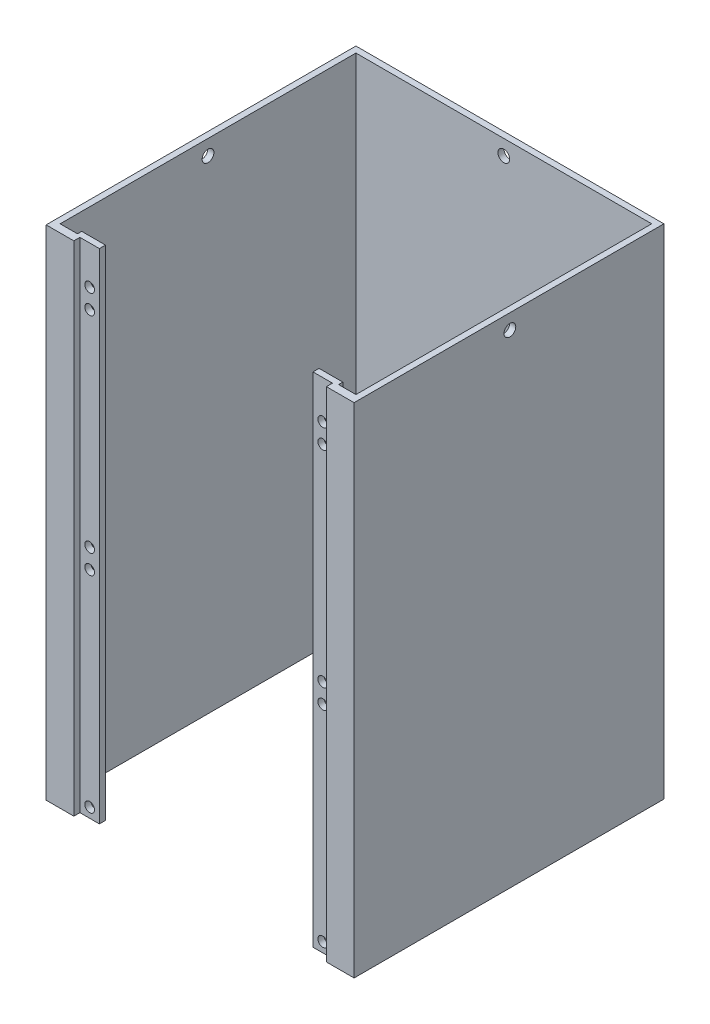
SolidWorks part; units mm, degrees
ref_plane "Front Plane" through (0, 0, 0) normal (0, 0, 1) x (1, 0, 0)
ref_plane "Top Plane" through (0, 0, 0) normal (0, 1, 0) x (1, 0, 0)
ref_plane "Right Plane" through (0, 0, 0) normal (1, 0, 0) x (0, 0, -1)
sketch "Sketch1" plane through (0, 0, 0) normal (0, 1, 0) x (1, 0, 0)
  line L0 (0, -0.603) -> (0, 101.206)
  line L1 (0, 101.206) -> (101.206, 101.206)
  line L2 (101.206, 101.206) -> (101.206, -0.6)
  line L3 (101.206, -0.6) -> (91.5, -0.6)
  line L4 (91.5, -0.6) -> (91.5, 1.4)
  line L5 (91.5, 1.4) -> (85.703, 1.4)
  line L6 (85.703, 1.4) -> (85.703, 3.4)
  line L7 (85.703, 3.4) -> (93.5, 3.4)
  line L8 (93.5, 3.4) -> (93.5, 2)
  line L9 (93.5, 2) -> (99.206, 2)
  line L10 (99.206, 2) -> (99.206, 99.206)
  line L11 (99.206, 99.206) -> (2, 99.206)
  line L12 (2, 99.206) -> (2, 2)
  line L13 (2, 2) -> (7.706, 2)
  line L14 (7.706, 2) -> (7.706, 3.397)
  line L15 (7.706, 3.397) -> (15.503, 3.397)
  line L16 (15.503, 3.397) -> (15.503, 1.397)
  line L17 (15.503, 1.397) -> (9.706, 1.397)
  line L18 (9.706, 1.397) -> (9.706, -0.603)
  line L19 (9.706, -0.603) -> (0, -0.603)
  dimension "D1" = 90
  dimension "D2" = 2
  dimension "D3" = 2
  dimension "D4" = 2
  dimension "D5" = 2
  dimension "D6" = 2
  dimension "D7" = 9.706
  dimension "D8" = 2
  dimension "D9" = 2
  dimension "D10" = 9.706
  dimension "D11" = 2
extrude "Boss-Extrude1" add sketch "Sketch1" along normal blind 327.5
sketch "Sketch7" plane through (0, 327.5, 0) normal (0, 1, 0) x (1, 0, 0)
  line L0 (0, -0.603) -> (9.706, -0.603) construction
  line L1 (9.103, -0.603) -> (92.103, -0.603)
  line L2 (9.103, -0.603) -> (9.103, 1.397)
  line L3 (9.103, 1.397) -> (92.103, 1.397)
  line L4 (92.103, -0.603) -> (92.103, 1.397)
  line L7 (101.206, -0.6) -> (101.206, 101.206) construction
  dimension "D1" = 83
  dimension "D2" = 9.103
  dimension "D3" = 2
extrude "Cut-Extrude7" cut sketch "Sketch7" against normal blind 203
sketch "Sketch2" plane through (0, 0, -1.397) normal (0, 0, 1) x (1, 0, 0)
  line L0 (9.103, 327.5) -> (15.503, 327.5) construction
  line L1 (15.503, 327.5) -> (15.503, 0) construction
  line L2 (85.703, 327.5) -> (85.703, 0) construction
  line L3 (85.703, 327.5) -> (91.5, 327.5) construction
  line L4 (9.706, 0) -> (15.503, 0) construction
  circle A0 centre (12.303, 314.9) radius 1.6
  circle A1 centre (12.303, 308.5) radius 1.6
  circle A2 centre (88.903, 314.9) radius 1.6
  circle A3 centre (88.903, 308.5) radius 1.6
  circle A4 centre (12.303, 240.925) radius 1.6
  circle A5 centre (12.303, 234.525) radius 1.6
  circle A6 centre (88.903, 240.925) radius 1.6
  circle A7 centre (88.903, 234.525) radius 1.6
  circle A8 centre (12.303, 166.95) radius 1.6
  circle A9 centre (12.303, 160.55) radius 1.6
  circle A10 centre (88.903, 166.95) radius 1.6
  circle A11 centre (88.903, 160.55) radius 1.6
  circle A12 centre (12.303, 92.975) radius 1.6
  circle A13 centre (12.303, 86.575) radius 1.6
  circle A14 centre (88.903, 92.975) radius 1.6
  circle A15 centre (88.903, 86.575) radius 1.6
  circle A16 centre (12.303, 19) radius 1.6
  circle A17 centre (12.303, 12.6) radius 1.6
  circle A18 centre (88.903, 19) radius 1.6
  circle A19 centre (88.903, 12.6) radius 1.6
  dimension "D1" = 3.2
  dimension "D2" = 3.2
  dimension "D3" = 12.6
  dimension "D4" = 6.4
  dimension "D5" = 3.2
  dimension "D6" = 3.2
  dimension "D8" = 3.2
  dimension "D9" = 3.2
  dimension "D10" = 12.6
  dimension "D12" = 12.6
  dimension "D7" = 2
  dimension "D11" = 5
extrude "Cut-Extrude2" cut sketch "Sketch2" against normal blind 10
sketch "Sketch3" plane through (101.206, 0, 0) normal (1, 0, 0) x (0, 0, -1)
  line L0 (-0.6, 327.5) -> (101.206, 327.5) construction
  line L3 (-0.6, 0) -> (101.206, 0) construction
  line L4 (2, 327.5) -> (2, 0) construction
  line L5 (99.206, 327.5) -> (99.206, 0) construction
  circle A0 centre (50.603, 322.524) radius 1.93
  circle A1 centre (50.603, 4.976) radius 1.93
  dimension "D1" = 3.86
  dimension "D7" = 3.86
  dimension "D2" = 4.976
  dimension "D3" = 48.603
  dimension "D4" = 48.603
  dimension "D5" = 48.603
  dimension "D6" = 4.976
  dimension "D8" = 48.603
extrude "Cut-Extrude3" cut sketch "Sketch3" against normal blind 102
sketch "Sketch4" plane through (0, 0, -101.206) normal (0, 0, -1) x (-1, 0, 0)
  line L0 (-101.206, 327.5) -> (0, 327.5) construction
  line L2 (-101.206, 0) -> (0, 0) construction
  line L3 (-2, 327.5) -> (-2, 0) construction
  line L4 (-99.206, 327.5) -> (-99.206, 0) construction
  circle A0 centre (-50.603, 322.524) radius 1.93
  circle A1 centre (-50.603, 4.976) radius 1.93
  dimension "D1" = 3.86
  dimension "D2" = 3.86
  dimension "D3" = 4.976
  dimension "D4" = 48.603
  dimension "D5" = 4.976
  dimension "D6" = 48.603
  dimension "D7" = 48.603
  dimension "D8" = 48.603
extrude "Cut-Extrude4" cut sketch "Sketch4" against normal blind 10
sketch "Sketch5" plane through (0, 0, 0) normal (-1, 0, 0) x (0, 0, 1)
  line L0 (-101.206, 327.5) -> (-101.206, 0) construction
  line L1 (29.0457, 0) -> (-101.206, 0)
  line L2 (29.0457, 0) -> (29.0457, 163.75)
  line L3 (29.0457, 163.75) -> (-101.206, 163.75)
  line L4 (-101.206, 0) -> (-101.206, 163.75)
  line L5 (-101.206, 327.5) -> (0.603, 327.5) construction
  dimension "D1" = 163.75
  dimension "D2" = 163.75
extrude "Cut-Extrude6" cut sketch "Sketch5" against normal blind 231 contours L3 L4 L1 L2
